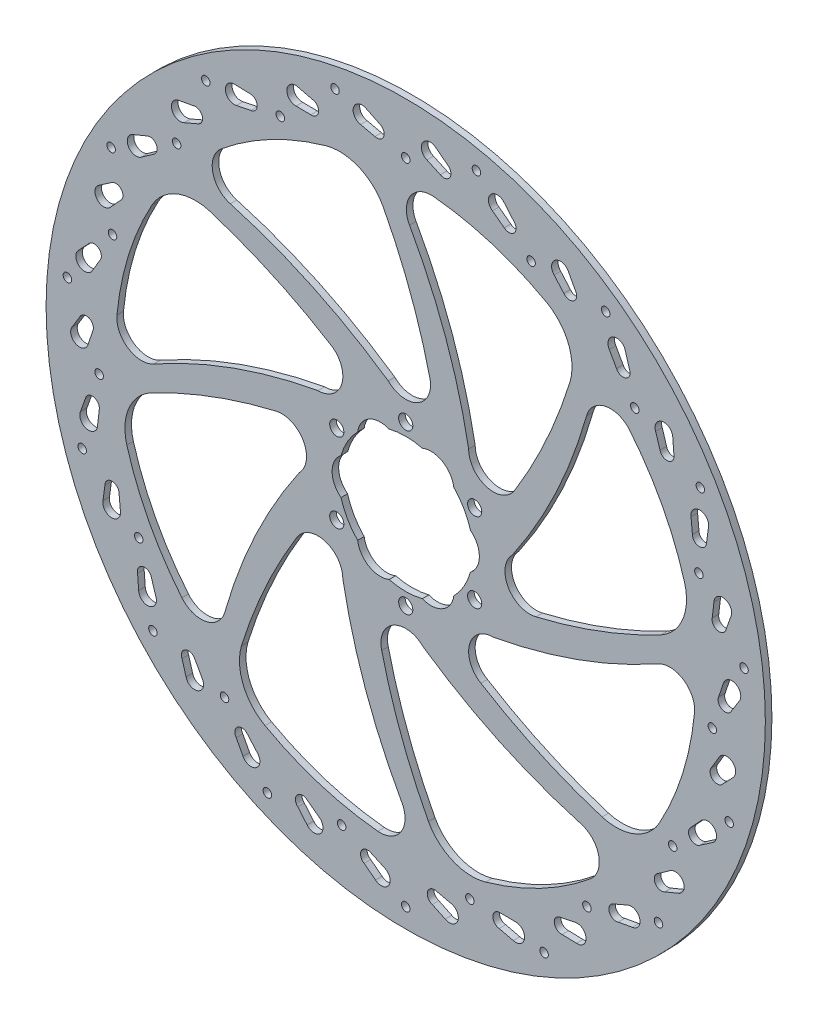
SolidWorks part; units mm, degrees
material "Chrome Stainless Steel"
ref_plane "Plan de face" through (0, 0, 0) normal (0, 0, 1) x (1, 0, 0)
ref_plane "Plan de dessus" through (0, 0, 0) normal (0, 1, 0) x (1, 0, 0)
ref_plane "Plan de droite" through (0, 0, 0) normal (1, 0, 0) x (0, 0, -1)
sketch "Sketch1" plane through (0, 0, 0) normal (0, 0, 1) x (1, 0, 0)
  line L0 (11.7494, 91.2536) -> (8.3288, 93.8934)
  line L1 (9.7648, 87.7806) -> (5.9882, 89.5132)
  line L2 (30.4653, 86.8166) -> (27.6683, 90.1099)
  line L3 (27.8021, 83.8322) -> (24.4682, 86.3121)
  line L4 (-7.48, 91.7023) -> (-11.3747, 93.5732)
  line L5 (47.8498, 78.5854) -> (45.7986, 82.3882)
  line L6 (44.6242, 76.2198) -> (41.8788, 79.3388)
  line L7 (-8.6992, 87.8926) -> (-12.7535, 88.8022)
  line L8 (63.143, 66.9196) -> (61.9273, 71.0658)
  line L9 (59.4961, 65.2764) -> (57.4591, 68.898)
  line L10 (75.6765, 52.329) -> (75.3494, 56.6374)
  line L11 (71.7677, 51.48) -> (70.5282, 55.446)
  line L12 (84.9026, 35.4515) -> (85.4784, 39.7337)
  line L13 (80.9026, 35.4337) -> (80.5148, 39.5707)
  line L14 (90.4181, 17.0245) -> (91.8716, 21.0935)
  line L15 (86.5018, 17.8388) -> (86.9826, 21.966)
  line L16 (91.9818, -2.1465) -> (94.2496, 1.5314)
  line L17 (88.3204, -0.5358) -> (89.6488, 3.4013)
  line L18 (89.5255, -21.2236) -> (92.5084, -18.0977)
  line L19 (86.279, -18.8869) -> (88.3969, -15.3121)
  line L20 (83.1565, -39.3733) -> (86.7242, -36.9358)
  line L21 (80.4668, -36.4126) -> (83.2817, -33.3562)
  line L22 (73.1532, -55.8021) -> (77.1496, -54.1596)
  line L23 (71.1378, -52.3469) -> (74.5266, -49.9425)
  line L24 (59.9527, -69.7921) -> (64.2033, -69.0164)
  line L25 (58.6997, -65.9934) -> (62.5144, -64.3461)
  line L26 (44.132, -80.7318) -> (48.451, -80.8569)
  line L27 (43.6962, -76.7556) -> (47.77, -75.9375)
  line L28 (26.3825, -88.1432) -> (30.5811, -89.1635)
  line L29 (26.783, -84.1633) -> (30.9378, -84.21)
  line L30 (7.48, -91.7023) -> (11.3747, -93.5732)
  line L31 (8.6992, -87.8926) -> (12.7535, -88.8022)
  line L32 (-11.7494, -91.2536) -> (-8.3288, -93.8934)
  line L33 (-9.7648, -87.7806) -> (-5.9882, -89.5132)
  line L34 (-30.4653, -86.8166) -> (-27.6683, -90.1099)
  line L35 (-27.8021, -83.8322) -> (-24.4682, -86.3121)
  line L36 (-47.8498, -78.5854) -> (-45.7986, -82.3882)
  line L37 (-44.6242, -76.2198) -> (-41.8788, -79.3388)
  line L38 (-63.143, -66.9196) -> (-61.9273, -71.0658)
  line L39 (-59.4961, -65.2764) -> (-57.4591, -68.898)
  line L40 (-75.6765, -52.329) -> (-75.3494, -56.6374)
  line L41 (-71.7677, -51.48) -> (-70.5282, -55.446)
  line L42 (-84.9026, -35.4515) -> (-85.4784, -39.7337)
  line L43 (-80.9026, -35.4337) -> (-80.5148, -39.5707)
  line L44 (-90.4181, -17.0245) -> (-91.8716, -21.0935)
  line L45 (-86.5018, -17.8388) -> (-86.9826, -21.966)
  line L46 (-91.9818, 2.1465) -> (-94.2496, -1.5314)
  line L47 (-88.3204, 0.5358) -> (-89.6488, -3.4013)
  line L48 (-89.5255, 21.2236) -> (-92.5084, 18.0977)
  line L49 (-86.279, 18.8869) -> (-88.3969, 15.3121)
  line L50 (-83.1565, 39.3733) -> (-86.7242, 36.9358)
  line L51 (-80.4668, 36.4126) -> (-83.2817, 33.3562)
  line L52 (-73.1532, 55.8021) -> (-77.1496, 54.1596)
  line L53 (-71.1378, 52.3469) -> (-74.5266, 49.9425)
  line L54 (-59.9527, 69.7921) -> (-64.2033, 69.0164)
  line L55 (-58.6997, 65.9934) -> (-62.5144, 64.3461)
  line L56 (-44.132, 80.7318) -> (-48.451, 80.8569)
  line L57 (-43.6962, 76.7556) -> (-47.77, 75.9375)
  line L58 (-26.3825, 88.1432) -> (-30.5811, 89.1635)
  line L59 (-26.783, 84.1633) -> (-30.9378, 84.21)
  line L60 (0, 18.97) -> (0, 25.9709) construction
  circle A0 centre (0, 0) radius 101.5
  arc A1 (13.5719, -13.2539) -> (18.2641, -5.1266) centre (0, 0) ccw
  arc A2 (18.2641, 5.1266) -> (13.5719, 13.2539) centre (0, 0) ccw
  arc A3 (4.6923, 18.3805) -> (-4.6923, 18.3805) centre (0, 0) ccw
  arc A6 (-13.5719, 13.2539) -> (-18.2641, 5.1266) centre (0, 0) ccw
  arc A7 (-18.2641, -5.1266) -> (-13.5719, -13.2539) centre (0, 0) ccw
  arc A9 (4.6923, -18.3805) -> (13.5719, -13.2539) centre (7.1447, -12.375) ccw
  arc A10 (18.2641, -5.1266) -> (18.2641, 5.1266) centre (14.2894, 0) ccw
  arc A11 (13.5719, 13.2539) -> (4.6923, 18.3805) centre (7.1447, 12.375) ccw
  arc A12 (-4.6923, 18.3805) -> (-13.5719, 13.2539) centre (-7.1447, 12.375) ccw
  arc A13 (-18.2641, 5.1266) -> (-18.2641, -5.1266) centre (-14.2894, 0) ccw
  circle A16 centre (0, -96) radius 1.2
  arc A19 (-13.5719, -13.2539) -> (-4.6923, -18.3805) centre (-7.1447, -12.375) ccw
  arc A21 (-49.5229, 51.0449) -> (-4.9497, 30.0502) centre (-90.2856, -93.3102) cw
  arc A22 (17.7487, 24.7487) -> (30.7822, 21.1994) centre (24.7487, 24.7487) ccw
  circle A23 centre (-39.0467, -87.7004) radius 1.2
  arc A24 (-22.5455, 78.7108) -> (-52.0725, 63.1834) centre (0, 0) ccw
  arc A25 (46.3594, 55.4206) -> (39.7148, 71.599) centre (32.924, 59.3563) ccw
  arc A26 (46.3594, 55.4206) -> (30.7822, 21.1994) centre (-96.8744, 99.9637) cw
  arc A27 (7.8566, 81.4983) -> (1.0763, 71.1122) centre (7.1849, 74.5306) ccw
  arc A28 (-6.4072, 71.9693) -> (6.776, 36.7565) centre (-139.1855, 2.1845) cw
  arc A29 (39.7148, 71.599) -> (7.8566, 81.4983) centre (0, 0) ccw
  arc A30 (1.0763, 71.1122) -> (17.7487, 24.7487) centre (-129.8218, -2.1387) cw
  arc A31 (-4.6923, -18.3805) -> (4.6923, -18.3805) centre (0, 0) ccw
  circle A32 centre (-71.3419, -64.2365) radius 1.2
  arc A33 (-63.1834, -52.0725) -> (-51.0449, -49.5229) centre (-57.7815, -47.6206) ccw
  arc A34 (-6.4072, 71.9693) -> (-22.5455, 78.7108) centre (-18.6905, 65.252) ccw
  arc A35 (78.7108, 22.5455) -> (63.1834, 52.0725) centre (0, 0) ccw
  arc A36 (-17.7487, -24.7487) -> (-30.7822, -21.1994) centre (-24.7487, -24.7487) ccw
  arc A37 (4.9497, -30.0503) -> (-6.776, -36.7565) centre (0, -35) ccw
  arc A38 (6.4072, -71.9693) -> (22.5455, -78.7108) centre (18.6905, -65.252) ccw
  arc A39 (6.4072, -71.9693) -> (-6.776, -36.7565) centre (139.1855, -2.1845) cw
  arc A40 (22.5455, -78.7108) -> (52.0725, -63.1834) centre (0, 0) ccw
  arc A41 (-52.0725, 63.1834) -> (-49.5229, 51.0449) centre (-47.6206, 57.7815) ccw
  arc A42 (-4.9497, 30.0502) -> (6.776, 36.7565) centre (0, 35) ccw
  arc A43 (63.1834, 52.0725) -> (51.0449, 49.5229) centre (57.7815, 47.6206) ccw
  circle A44 centre (0, 22.4704) radius 2
  circle A45 centre (-91.3014, -29.6656) radius 1.2
  circle A46 centre (-95.4741, 10.0347) radius 1.2
  circle A47 centre (-83.1384, 48) radius 1.2
  circle A48 centre (-56.4274, 77.6656) radius 1.2
  circle A49 centre (-19.9595, 93.9022) radius 1.2
  circle A50 centre (19.9595, 93.9022) radius 1.2
  circle A51 centre (56.4274, 77.6656) radius 1.2
  arc A52 (51.0449, 49.5229) -> (30.0502, 4.9497) centre (-93.3102, 90.2856) cw
  arc A53 (30.0502, 4.9497) -> (36.7565, -6.776) centre (35, 0) ccw
  arc A54 (71.9693, 6.4072) -> (78.7108, 22.5455) centre (65.252, 18.6905) ccw
  circle A55 centre (19.46, 11.2352) radius 2
  arc A56 (71.9693, 6.4072) -> (36.7565, -6.776) centre (2.1845, 139.1855) cw
  arc A57 (55.4206, -46.3594) -> (71.599, -39.7148) centre (59.3563, -32.924) ccw
  arc A58 (55.4206, -46.3594) -> (21.1994, -30.7822) centre (99.9637, 96.8744) cw
  arc A59 (24.7487, -17.7487) -> (21.1994, -30.7822) centre (24.7487, -24.7487) ccw
  arc A60 (81.4983, -7.8566) -> (71.1122, -1.0763) centre (74.5306, -7.1849) ccw
  arc A61 (71.599, -39.7148) -> (81.4983, -7.8566) centre (0, 0) ccw
  arc A62 (71.1122, -1.0763) -> (24.7487, -17.7487) centre (-2.1387, 129.8218) cw
  circle A63 centre (19.46, -11.2352) radius 2
  circle A64 centre (83.1384, 48) radius 1.2
  circle A65 centre (95.4741, 10.0347) radius 1.2
  circle A66 centre (91.3014, -29.6656) radius 1.2
  circle A67 centre (71.3419, -64.2365) radius 1.2
  circle A68 centre (39.0467, -87.7004) radius 1.2
  arc A69 (-55.4206, 46.3594) -> (-21.1994, 30.7821) centre (-99.9637, -96.8744) cw
  arc A70 (-71.599, 39.7148) -> (-81.4983, 7.8566) centre (0, 0) ccw
  arc A71 (-71.9693, -6.4072) -> (-78.7108, -22.5455) centre (-65.252, -18.6905) ccw
  arc A72 (-24.7487, 17.7487) -> (-21.1994, 30.7821) centre (-24.7487, 24.7487) ccw
  circle A73 centre (18.0883, -85.0988) radius 1.2
  arc A74 (49.5229, -51.045) -> (4.9497, -30.0503) centre (90.2856, 93.3102) cw
  circle A75 centre (0, -22.4704) radius 2
  arc A76 (52.0725, -63.1834) -> (49.5229, -51.045) centre (47.6206, -57.7815) ccw
  arc A77 (-46.3594, -55.4206) -> (-30.7822, -21.1994) centre (96.8744, -99.9637) cw
  arc A78 (-46.3594, -55.4206) -> (-39.7148, -71.599) centre (-32.924, -59.3563) ccw
  arc A79 (-39.7148, -71.599) -> (-7.8566, -81.4983) centre (0, 0) ccw
  arc A80 (-1.0763, -71.1122) -> (-17.7487, -24.7487) centre (129.8218, 2.1387) cw
  arc A81 (-7.8566, -81.4983) -> (-1.0763, -71.1122) centre (-7.1849, -74.5306) ccw
  circle A82 centre (-19.46, -11.2352) radius 2
  arc A83 (-78.7108, -22.5455) -> (-63.1834, -52.0725) centre (0, 0) ccw
  arc A84 (-71.9693, -6.4072) -> (-36.7565, 6.776) centre (-2.1845, -139.1855) cw
  arc A85 (-51.0449, -49.5229) -> (-30.0502, -4.9497) centre (93.3102, -90.2856) cw
  arc A86 (-30.0502, -4.9497) -> (-36.7565, 6.776) centre (-35, 0) ccw
  circle A87 centre (-19.46, 11.2352) radius 2
  arc A88 (-81.4983, 7.8566) -> (-71.1122, 1.0763) centre (-74.5306, 7.1849) ccw
  arc A89 (-55.4206, 46.3594) -> (-71.599, 39.7148) centre (-59.3563, 32.924) ccw
  arc A91 (-71.1122, 1.0763) -> (-24.7487, 17.7487) centre (2.1387, -129.8218) cw
  circle A92 centre (-18.0883, -85.0988) radius 1.2
  circle A93 centre (-51.1373, -70.3845) radius 1.2
  circle A94 centre (-75.3442, -43.5) radius 1.2
  circle A95 centre (-86.5234, -9.094) radius 1.2
  circle A96 centre (-82.7419, 26.8845) radius 1.2
  circle A97 centre (-64.6536, 58.2144) radius 1.2
  circle A98 centre (-35.3861, 79.4785) radius 1.2
  circle A99 centre (0, 87) radius 1.2
  circle A100 centre (35.3861, 79.4785) radius 1.2
  circle A101 centre (64.6536, 58.2144) radius 1.2
  circle A102 centre (82.7419, 26.8845) radius 1.2
  circle A103 centre (86.5234, -9.094) radius 1.2
  circle A104 centre (75.3442, -43.5) radius 1.2
  circle A105 centre (51.1373, -70.3845) radius 1.2
  arc A106 (9.7648, 87.7806) -> (11.7494, 91.2536) centre (10.7571, 89.5171) ccw
  arc A107 (-8.6992, 87.8926) -> (-7.48, 91.7023) centre (-8.0896, 89.7975) ccw
  arc A108 (-11.1479, 93.4643) -> (-12.7535, 88.8022) centre (-12.3425, 91.2681) ccw
  arc A109 (8.528, 93.7396) -> (5.9882, 89.5132) centre (6.9029, 91.8399) ccw
  arc A110 (27.8021, 83.8322) -> (30.4653, 86.8166) centre (29.1337, 85.3244) ccw
  arc A111 (27.8312, 89.9181) -> (24.4682, 86.3121) centre (25.8467, 88.3977) ccw
  arc A112 (44.6242, 76.2198) -> (47.8498, 78.5854) centre (46.237, 77.4026) ccw
  arc A113 (45.9181, 82.1668) -> (41.8788, 79.3388) centre (43.6608, 81.0922) ccw
  arc A114 (59.4961, 65.2764) -> (63.143, 66.9196) centre (61.3195, 66.098) ccw
  arc A115 (61.9981, 70.8243) -> (57.4591, 68.898) centre (59.5667, 70.2426) ccw
  arc A116 (71.7677, 51.48) -> (75.6765, 52.329) centre (73.7221, 51.9045) ccw
  arc A117 (75.3685, 56.3865) -> (70.5282, 55.446) centre (72.8693, 56.323) ccw
  arc A118 (80.9026, 35.4337) -> (84.9026, 35.4515) centre (82.9026, 35.4426) ccw
  arc A119 (85.4449, 39.4844) -> (80.5148, 39.5707) centre (82.9871, 39.9418) ccw
  arc A120 (86.5018, 17.8388) -> (90.4181, 17.0245) centre (88.4599, 17.4317) ccw
  arc A121 (91.787, 20.8565) -> (86.9826, 21.966) centre (89.478, 21.815) ccw
  arc A122 (88.3204, -0.5358) -> (91.9818, -2.1465) centre (90.1511, -1.3411) ccw
  arc A123 (94.1175, 1.3172) -> (89.6488, 3.4013) centre (92.0583, 2.7347) ccw
  arc A124 (86.279, -18.8869) -> (89.5255, -21.2236) centre (87.9023, -20.0553) ccw
  arc A125 (92.3347, -18.2797) -> (88.3969, -15.3121) centre (90.6152, -16.465) ccw
  arc A126 (80.4668, -36.4126) -> (83.1565, -39.3733) centre (81.8117, -37.8929) ccw
  arc A127 (86.5164, -37.0778) -> (83.2817, -33.3562) centre (85.2118, -34.9452) ccw
  arc A128 (71.1378, -52.3469) -> (73.1532, -55.8021) centre (72.1455, -54.0745) ccw
  arc A129 (76.9169, -54.2553) -> (74.5266, -49.9425) centre (76.0842, -51.8981) ccw
  arc A130 (58.6997, -65.9934) -> (59.9527, -69.7921) centre (59.3262, -67.8927) ccw
  arc A131 (63.9558, -69.0616) -> (62.5144, -64.3461) centre (63.6313, -66.5827) ccw
  arc A132 (43.6962, -76.7556) -> (44.132, -80.7318) centre (43.9141, -78.7437) ccw
  arc A133 (48.1995, -80.8496) -> (47.77, -75.9375) centre (48.3975, -78.3575) ccw
  arc A134 (26.783, -84.1633) -> (26.3825, -88.1432) centre (26.5828, -86.1532) ccw
  arc A135 (30.3366, -89.1041) -> (30.9378, -84.21) centre (31.0485, -86.7076) ccw
  arc A136 (8.6992, -87.8926) -> (7.48, -91.7023) centre (8.0896, -89.7975) ccw
  arc A137 (11.1479, -93.4643) -> (12.7535, -88.8022) centre (12.3425, -91.2681) ccw
  arc A138 (-9.7648, -87.7806) -> (-11.7494, -91.2536) centre (-10.7571, -89.5171) ccw
  arc A139 (-8.528, -93.7396) -> (-5.9882, -89.5132) centre (-6.9029, -91.8399) ccw
  arc A140 (-27.8021, -83.8322) -> (-30.4653, -86.8166) centre (-29.1337, -85.3244) ccw
  arc A141 (-27.8312, -89.9181) -> (-24.4682, -86.3121) centre (-25.8467, -88.3977) ccw
  arc A142 (-44.6242, -76.2198) -> (-47.8498, -78.5854) centre (-46.237, -77.4026) ccw
  arc A143 (-45.9181, -82.1668) -> (-41.8788, -79.3388) centre (-43.6608, -81.0922) ccw
  arc A144 (-59.4961, -65.2764) -> (-63.143, -66.9196) centre (-61.3195, -66.098) ccw
  arc A145 (-61.9981, -70.8243) -> (-57.4591, -68.898) centre (-59.5667, -70.2426) ccw
  arc A146 (-71.7677, -51.48) -> (-75.6765, -52.329) centre (-73.7221, -51.9045) ccw
  arc A147 (-75.3685, -56.3865) -> (-70.5282, -55.446) centre (-72.8693, -56.323) ccw
  arc A148 (-80.9026, -35.4337) -> (-84.9026, -35.4515) centre (-82.9026, -35.4426) ccw
  arc A149 (-85.4449, -39.4844) -> (-80.5148, -39.5707) centre (-82.9871, -39.9418) ccw
  arc A150 (-86.5018, -17.8388) -> (-90.4181, -17.0245) centre (-88.4599, -17.4317) ccw
  arc A151 (-91.787, -20.8565) -> (-86.9826, -21.966) centre (-89.478, -21.815) ccw
  arc A152 (-88.3204, 0.5358) -> (-91.9818, 2.1465) centre (-90.1511, 1.3411) ccw
  arc A153 (-94.1175, -1.3172) -> (-89.6488, -3.4013) centre (-92.0583, -2.7347) ccw
  arc A154 (-86.279, 18.8869) -> (-89.5255, 21.2236) centre (-87.9023, 20.0553) ccw
  arc A155 (-92.3347, 18.2797) -> (-88.3969, 15.3121) centre (-90.6152, 16.465) ccw
  arc A156 (-80.4668, 36.4126) -> (-83.1565, 39.3733) centre (-81.8117, 37.8929) ccw
  arc A157 (-86.5164, 37.0778) -> (-83.2817, 33.3562) centre (-85.2118, 34.9452) ccw
  arc A158 (-71.1378, 52.3469) -> (-73.1532, 55.8021) centre (-72.1455, 54.0745) ccw
  arc A159 (-76.9169, 54.2553) -> (-74.5266, 49.9425) centre (-76.0842, 51.8981) ccw
  arc A160 (-58.6997, 65.9934) -> (-59.9527, 69.7921) centre (-59.3262, 67.8927) ccw
  arc A161 (-63.9558, 69.0616) -> (-62.5144, 64.3461) centre (-63.6313, 66.5827) ccw
  arc A162 (-43.6962, 76.7556) -> (-44.132, 80.7318) centre (-43.9141, 78.7437) ccw
  arc A163 (-48.1995, 80.8496) -> (-47.77, 75.9375) centre (-48.3975, 78.3575) ccw
  arc A164 (-26.783, 84.1633) -> (-26.3825, 88.1432) centre (-26.5828, 86.1532) ccw
  arc A165 (-30.3366, 89.1041) -> (-30.9378, 84.21) centre (-31.0485, 86.7076) ccw
  circle A188 centre (0, 0) radius 22.4704 construction
  dimension "D1" = 37.94
  dimension "D2" = 4
extrude "Extrude1" add sketch "Sketch1" along normal blind 1.85 contours A0 A165 L58 A164 L59 A163 L56 A162 L57 A161 L54 A160 L55 A159 L52 A158 L53 A157 L50 A156 L51 A155 L48 A154 L49 A153 L46 A152 L47 A151 L44 A150 L45 A149
